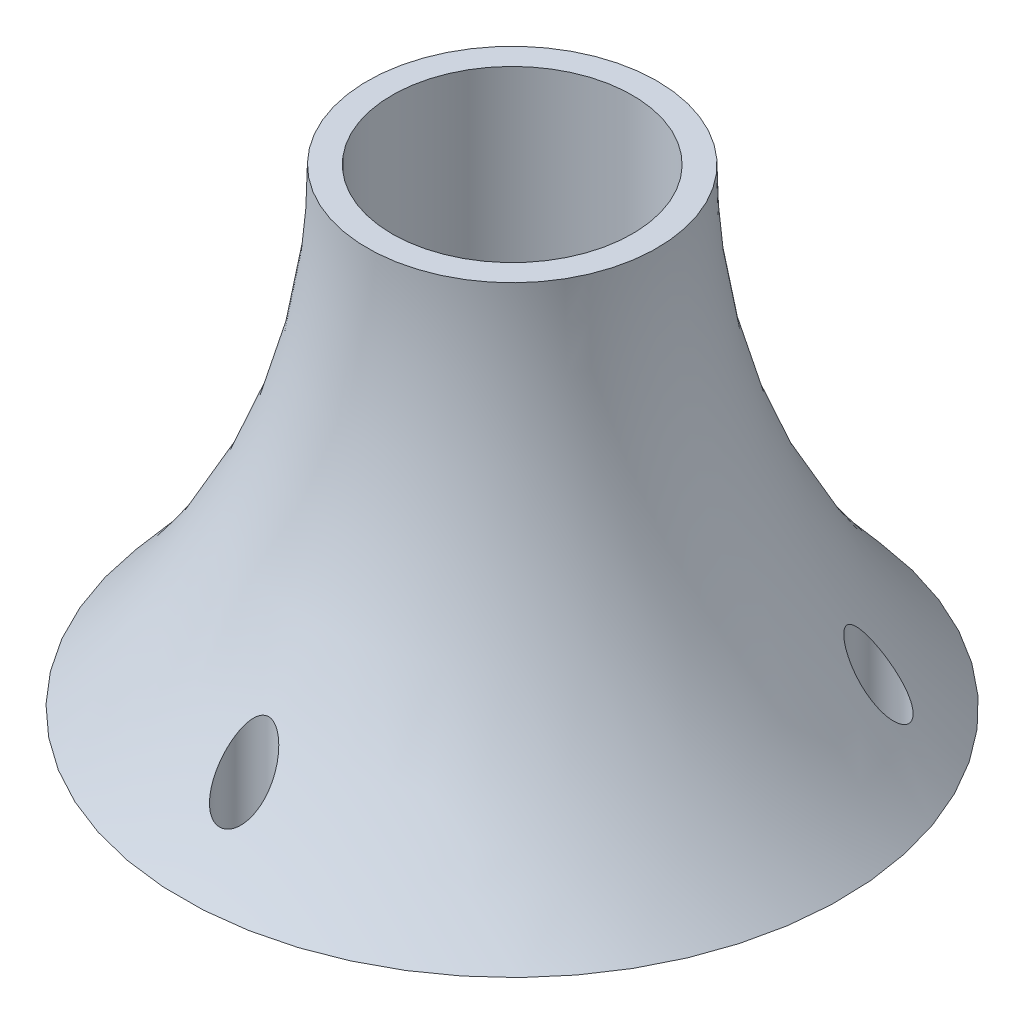
SolidWorks part; units mm, degrees
ref_plane "Front Plane" through (0, 0, 0) normal (0, 0, 1) x (1, 0, 0)
ref_plane "Top Plane" through (0, 0, 0) normal (0, 1, 0) x (1, 0, 0)
ref_plane "Right Plane" through (0, 0, 0) normal (1, 0, 0) x (0, 0, -1)
sketch "Sketch1" plane through (0, 0, 0) normal (0, 1, 0) x (1, 0, 0)
  circle A0 centre (0, 0) radius 24.765
  circle A1 centre (0, 0) radius 29.845
  dimension "D1" = 49.53
  dimension "D2" = 5.08
extrude "Boss-Extrude1" add sketch "Sketch1" along normal blind 97.07
sketch "Sketch2" plane through (0, 0, 0) normal (0, -1, 0) x (1, 0, 0)
  circle A0 centre (0, 0) radius 24.765
  circle A1 centre (0, 0) radius 24.765 construction
sketch "Sketch3" plane through (0, 0, 0) normal (0, 0, 1) x (1, 0, 0)
  line L0 (0, 0) -> (0, 97.07) construction
  line L1 (-24.765, 0) -> (24.765, 0) construction
  line L2 (24.765, 97.07) -> (-24.765, 97.07) construction
  line L3 (0, 97.07) -> (29.845, 97.07) construction
  line L4 (29.845, 97.07) -> (-29.845, 97.07) construction
  line L5 (29.845, 0) -> (29.845, 97.07) construction
  line L6 (29.845, 97.07) -> (29.845, 0) construction
  line L7 (29.845, 0) -> (0, 0) construction
  line L8 (29.845, 0) -> (67.945, 0) construction
  line L9 (67.945, 0) -> (67.945, 97.07) construction
  line L10 (67.945, 97.07) -> (29.845, 97.07) construction
  line L11 (67.945, 0) -> (29.845, 0)
  line L12 (29.845, 0) -> (29.845, 97.07)
  arc A0 (29.845, 97.07) -> (67.945, 0) centre (172.551, 97.07) ccw
  dimension "D1" = 38.1
revolve "Revolve1" add sketch "Sketch3" angle 360 about L0
sketch "Sketch4" plane through (0, 0, 0) normal (0, -1, 0) x (1, 0, 0)
  line L0 (0, 0) -> (0, 67.945) construction
  line L1 (0, 24.765) -> (0, 67.945) construction
  line L2 (0, 24.765) -> (0, 67.945) construction
  line L3 (0, 0) -> (-58.8421, -33.9725) construction
  circle A0 centre (0, 0) radius 67.945 construction
  circle A1 centre (0, 0) radius 24.765 construction
  circle A2 centre (0, 0) radius 24.765
  circle A3 centre (0, 0) radius 55.245 construction
  circle A4 centre (0, 55.245) radius 5.05
  circle A5 centre (47.8436, -27.6225) radius 5.05
  circle A6 centre (-47.8436, -27.6225) radius 5.05
  point P14 (-45.4466, -31.4105)
  point P19 (0, 0)
  dimension "D1" = 12.7
  dimension "D2" = 10.1
  dimension "D4" = 120
  dimension "D3" = 3
extrude "Cut-Extrude1" cut sketch "Sketch4" against normal blind 95
